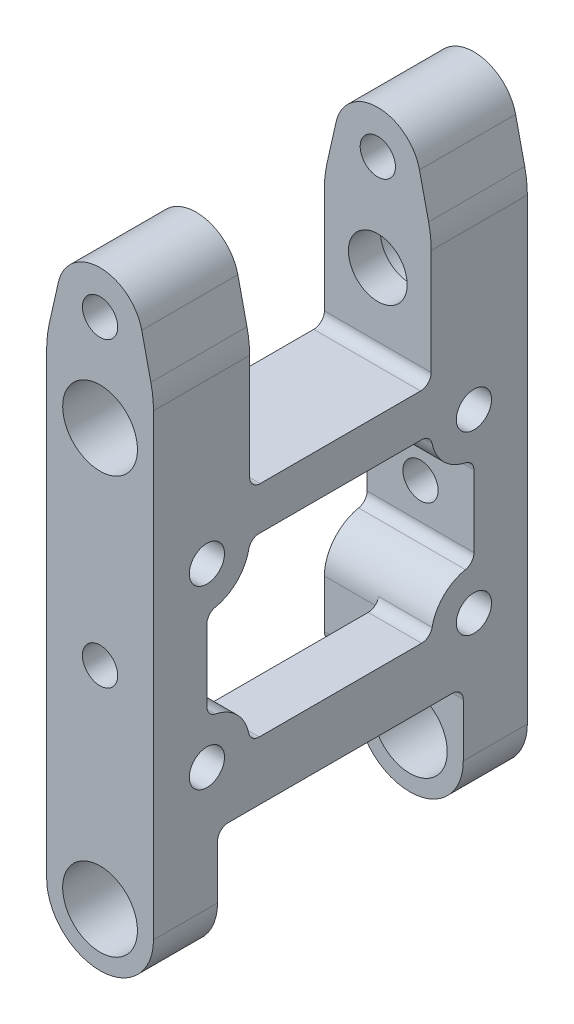
SolidWorks part; units mm, degrees
material "6061 合金"
ref_plane "前视基准面" through (0, 0, 0) normal (0, 0, 1) x (1, 0, 0)
ref_plane "上视基准面" through (0, 0, 0) normal (0, 1, 0) x (1, 0, 0)
ref_plane "右视基准面" through (0, 0, 0) normal (1, 0, 0) x (0, 0, -1)
sketch "草图1" plane through (0, 0, 0) normal (0, 0, 1) x (1, 0, 0)
  line L0 (-63.6974, 1.3001) -> (-160.5974, 1.3001) construction
  line L1 (-188.3974, -74.6999) -> (-196.8974, -74.6999) construction
  line L3 (-188.3974, 77.3001) -> (-188.3974, -74.6999) construction
  line L5 (-160.5974, 77.3001) -> (-160.5974, -74.6999) construction
  line L6 (-152.0974, 77.3001) -> (-160.5974, 77.3001) construction
  line L7 (-152.0974, 77.3001) -> (-152.0974, -74.6999) construction
  line L8 (-152.0974, -74.6999) -> (-160.5974, -74.6999) construction
  line L9 (-196.8974, 77.3001) -> (-196.8974, -74.6999) construction
  line L10 (-188.3974, 77.3001) -> (-196.8974, 77.3001) construction
  line L11 (55, 0) -> (-55, 0) construction
  line L12 (-146.0974, 20.8001) -> (-146.0974, -18.1999)
  line L13 (-63.6974, 22.3001) -> (-134.7974, 22.3001) construction
  line L14 (-63.6974, 22.3001) -> (-63.6974, -19.6999) construction
  line L15 (-63.6974, -19.6999) -> (-134.7974, -19.6999) construction
  line L16 (-134.7974, 22.3001) -> (-134.7974, -19.6999) construction
  line L17 (-146.0974, 20.8001) -> (-60, 39)
  line L18 (-146.0974, -18.1999) -> (-60, 0)
  line L19 (-60, 0) -> (-60, 39)
  line L20 (-124.0083, -11.4863) -> (-75, 64)
  line L21 (-138, 106.5) -> (-138, 78.0686) construction
  line L22 (-75, 64) -> (27.8173, 64) construction
  line L23 (-123.5947, -13.4431) -> (-124.0083, -11.4863) construction
  circle A0 centre (-60, 0) radius 5 construction
  circle A1 centre (-60, 0) radius 3
  point P14 (-146.0974, 1.3001)
  dimension "D12" = 10
  dimension "D15" = 5
  dimension "D21" = 6
  dimension "D1" = 96.9
  dimension "D2" = 27.8
  dimension "D3" = 44.8
  dimension "D4" = 152
  dimension "D5" = 88
  dimension "D6" = 42
  dimension "D7" = 71.1
  dimension "D8" = 39
  dimension "D9" = 11.3
  dimension "D10" = 110
  dimension "D11" = 15
  dimension "D13" = 23
  dimension "D14" = 2
  dimension "D16" = 1.3001
  dimension "D17" = 138
  dimension "D18" = 64
  dimension "D20" = 90
sketch "草图7" plane through (0, 0, 0) normal (1, 0, 0) x (0, 0, -1)
  line L0 (0, 55) -> (0, -55) construction
  line L1 (-256.6842, 0) -> (256.6842, 0) construction
  line L2 (-277.7004, -107.0971) -> (-27.9153, -28.7852) construction
  line L3 (-27.9153, -28.7852) -> (291.0502, -100.0411) construction
  line L4 (-201.3277, -98.6084) -> (-65.271, -11.8548) construction
  line L5 (-65.271, -11.8548) -> (42.2558, -180.4904) construction
  line L6 (42.2558, -180.4904) -> (281.3904, -28.0114) construction
  circle A0 centre (-186, 1.3001) radius 76
  circle A1 centre (186, 1.3001) radius 76
  dimension "D1" = 152
  dimension "D2" = 186
  dimension "D3" = 150
  dimension "D4" = 200
sketch "草图2" plane through (0, 0, 0) normal (0, 0, 1) x (1, 0, 0)
  line L1 (-65, 0) -> (-65, 44)
  line L3 (-55, 44) -> (-55, 0)
  line L4 (-65, 44) -> (-55, 44) construction
  line L6 (-65, 44) -> (-63.9024, 48.878)
  line L7 (-55, 44) -> (-56.0976, 48.878)
  circle A0 centre (-60, 0) radius 5 construction
  arc A1 (-65, 0) -> (-55, 0) centre (-60, 0) ccw
  circle A3 centre (-60, 39) radius 2.75
  circle A4 centre (-60, 0) radius 2.75
  arc A5 (-56.0976, 48.878) -> (-63.9024, 48.878) centre (-60, 48) ccw
  dimension "D1" = 8
  dimension "D2" = 5.5
  dimension "D3" = 9
  dimension "D4" = 4
extrude "凸台-拉伸1" add sketch "草图2" along normal mid plane 35
sketch "草图8" plane through (-55, 0, 0) normal (1, 0, 0) x (0, 0, -1)
  line L0 (-17.5, -5) -> (17.5, -5) construction
  line L5 (-17.5, 0) -> (-17.5, 44) construction
  line L7 (11.5, -5) -> (-11.5, -5)
  line L8 (11.5, -5) -> (11.5, 6)
  line L9 (11.5, 6) -> (-11.5, 6)
  line L10 (-11.5, -5) -> (-11.5, 6)
  line L16 (-17.5, 22) -> (17.5, 22) construction
  line L17 (17.5, 0) -> (17.5, 44) construction
  line L22 (-8.5, 52) -> (-8.5, 32)
  line L23 (8.5, 32) -> (-8.5, 32)
  line L24 (8.5, 52) -> (8.5, 32)
  line L30 (8.5, 52) -> (-8.5, 52)
  line L34 (17.5, 52) -> (-17.5, 52) construction
  point P3 (0, 32)
  point P12 (0, 6)
  dimension "D1" = 11
  dimension "D2" = 23
  dimension "D3" = 17
  dimension "D4" = 20
extrude "切除-拉伸2" cut sketch "草图8" against normal through all
sketch "草图3" plane through (0, 0, 17.5) normal (0, 0, 1) x (1, 0, 0)
  circle A2 centre (-60, 0) radius 3.5
  circle A5 centre (-60, 39) radius 3.5
  point P0 (-60, 39)
  dimension "D1" = 7
extrude "切除-拉伸1" cut sketch "草图3" against normal blind 6
hole_wizard "M4 螺纹孔1" positions "草图4" profile "草图6" tap size "M4" standard "GB" end condition up to next
sketch "草图4" plane through (-55, 0, 0) normal (1, 0, 0) x (0, 0, -1)
  line L0 (0, 5.5) -> (0, -5.5) construction
  line L10 (-17.5, 0) -> (-17.5, 44) construction
  line L11 (11.5, 6) -> (-11.5, 6) construction
  line L12 (-12.5, 28) -> (-12.5, 11.5) construction
  point P0 (-12.5, 11.5)
  point P8 (12.5, 11.5)
  point P51 (-12.5, 28)
  point P61 (12.5, 28)
  dimension "D1" = 5
  dimension "D2" = 5.5
  dimension "D3" = 16.5
cosmetic thread "孔螺蚊线1" parameters "D2"=4
cosmetic thread "孔螺蚊线2" parameters "D2"=4
sketch "草图6" plane through (-55, 11.5, 12.5) normal (0, 1, 0) x (0, 0, -1)
  line L0 (0, 0) -> (0, 10)
  line L1 (0, 10) -> (1.65, 10)
  line L2 (1.65, 10) -> (1.65, 0)
  line L5 (1.65, 0) -> (0, 0)
  line L11 (0, -6.35) -> (0, 107.95) construction
  dimension "通孔螺纹孔钻头直径" = 3.3
  dimension "通孔螺纹孔钻头深度" = 10
cosmetic thread "孔螺蚊线6" parameters "D2"=4
cosmetic thread "孔螺蚊线7" parameters "D2"=4
mirror "镜向1" about plane through (0, 0, 0) normal (0, 0, 1) of "切除-拉伸1"
sketch "草图11" plane through (-65, 0, 0) normal (-1, 0, 0) x (0, 0, 1)
  line L5 (-12.5, 24) -> (-12.5, 15.5)
  line L25 (-8.5, 28) -> (8.5, 28)
  line L28 (-8.5, 11.5) -> (8.5, 11.5)
  line L29 (0, -5.5) -> (0, 5.5) construction
  line L30 (12.5, 24) -> (12.5, 15.5)
  arc A4 (-8.5, 11.5) -> (-12.5, 15.5) centre (-12.5, 11.5) ccw
  arc A5 (8.5, 11.5) -> (12.5, 15.5) centre (12.5, 11.5) cw
  arc A6 (-12.5, 24) -> (-8.5, 28) centre (-12.5, 28) ccw
  arc A7 (12.5, 24) -> (8.5, 28) centre (12.5, 28) cw
  dimension "D4" = 4
  dimension "D3" = 25
extrude "切除-拉伸3" cut sketch "草图11" against normal through all
hole_wizard "M4 螺纹孔2" positions "草图12" profile "草图13" tap size "M4" standard "GB" end condition through all
sketch "草图12" plane through (0, 0, 17.5) normal (0, 0, 1) x (1, 0, 0)
  line L0 (-60, 15.5) -> (-60, 24) construction
  line L5 (-55, 15.5) -> (-65, 15.5) construction
  line L6 (-55, 24) -> (-65, 24) construction
  point P22 (-60, 19.75)
  point P60 (-60, 48)
sketch "草图13" plane through (-60, 19.75, 17.5) normal (1, 0, 0) x (0, -1, 0)
  line L0 (0, 0) -> (0, 35)
  line L1 (0, 35) -> (1.65, 35)
  line L2 (1.65, 35) -> (1.65, 0)
  line L5 (1.65, 0) -> (0, 0)
  line L11 (0, -6.35) -> (0, 107.95) construction
  dimension "通孔螺纹孔钻头直径" = 3.3
  dimension "通孔螺纹孔钻头深度" = 35
cosmetic thread "孔螺蚊线8" parameters "D2"=4
cosmetic thread "孔螺蚊线9" parameters "D2"=4
sketch "草图15" plane through (-65, 0, 0) normal (-1, 0, 0) x (0, 0, 1)
  line L0 (-11.5, 6) -> (11.5, 6) construction
  line L1 (-8.5, 11.5) -> (8.5, 11.5)
  line L2 (-8.5, 11.5) -> (-8.5, 6)
  line L3 (-8.5, 6) -> (8.5, 6)
  line L4 (8.5, 11.5) -> (8.5, 6)
extrude "切除-拉伸5" cut sketch "草图15" against normal blind 5
fillet "圆角1" radius 1 14 edges at (-60, 32, 8.5) (-60, 32, -8.5) (-60, 6, 11.5) (-60, 6, -11.5) (-62.5, 6, 8.5) (-62.5, 6, -8.5) (-60, 24, -12.5) (-60, 28, -8.5) (-60, 28, 8.5) (-60, 24, 12.5) (-57.5, 11.5, 8.5) (-57.5, 11.5, -8.5) (-60, 15.5, -12.5) (-60, 15.5, 12.5)
fillet "圆角2" radius 10 4 edges at (-65, 44, 13) (-55, 44, 13) (-55, 44, -13) (-65, 44, -13)
